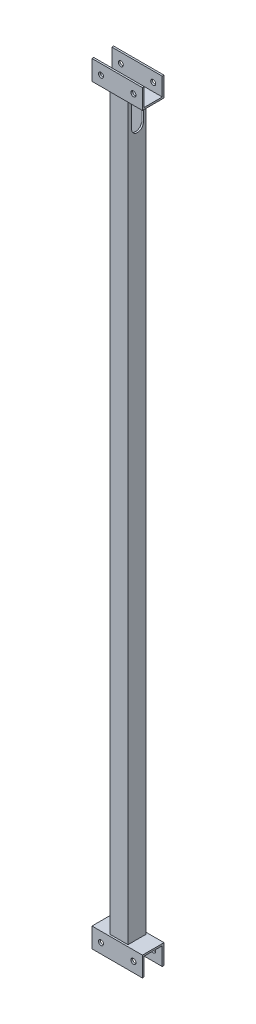
SolidWorks part; units mm, degrees
ref_plane "Front Plane" through (0, 0, 0) normal (0, 0, 1) x (1, 0, 0)
ref_plane "Top Plane" through (0, 0, 0) normal (0, 1, 0) x (1, 0, 0)
ref_plane "Right Plane" through (0, 0, 0) normal (1, 0, 0) x (0, 0, -1)
sketch "Sketch1" plane through (0, 0, 0) normal (0, 1, 0) x (1, 0, 0)
  line L1 (70, -15) -> (70, 45)
  line L2 (-70, -15) -> (-70, 45)
  line L3 (-70, 45) -> (70, 45)
  line L4 (-70, -15) -> (70, -15)
  point P4 (0, 0)
  dimension "D1" = 140
  dimension "D2" = 60
extrude "Boss-Extrude1" add sketch "Sketch1" against normal blind 5
sketch "Sketch2" plane through (0, -5, 0) normal (0, -1, 0) x (1, 0, 0)
  line L0 (-70, 15) -> (70, 15) construction
  line L1 (-70, 15) -> (70, 15)
  line L3 (-70, 10) -> (-70, 15)
  line L4 (70, 10) -> (70, 15)
  line L5 (70, 15) -> (70, -45) construction
  line L10 (-70, 10) -> (70, 10)
  line L15 (70, 15) -> (70, -45)
  line L16 (-930, -15) -> (49070, -15) construction
  line L17 (-70, -40) -> (70, -40)
  line L18 (-70, -40) -> (-70, -45)
  line L19 (-70, -45) -> (70, -45)
  line L20 (70, -40) -> (70, -45)
  point P6 (70, -15)
  line M6 (70, 15) -> (-70, 15)
  line M7 (-70, 15) -> (-70, -45)
  line M9 (70, -45) -> (70, 15)
  dimension "D1" = 140
  dimension "D2" = 5
sketch "Sketch3" plane through (0, 0, 15) normal (0, 0, 1) x (1, 0, 0)
  line L0 (0, -1000) -> (0, 49000) construction
  line L1 (0, 0) -> (0, -55) construction
  line L2 (45, -27.5) -> (-45, -27.5) construction
  point P8 (0, -27.5)
extrude "Boss-Extrude3" add sketch "Sketch2" along normal blind 50 contours L10 M7 M9 M6 | L19 L20 L17 L18
sketch "Sketch4" plane through (0, 0, 15) normal (0, 0, 1) x (1, 0, 0)
  line L4 (70, 0) -> (-70, 0)
  line L5 (-70, 0) -> (-70, -55)
  line L6 (-70, -55) -> (70, -55)
  line L7 (70, -55) -> (70, 0)
  line L8 (70, 0) -> (-70, 0)
  circle A0 centre (-45, -27.5) radius 7
  circle A1 centre (45, -27.5) radius 7
  point P2 (0, 0)
  point P4 (0, -27.5)
  dimension "D2" = 14
  dimension "D1" = 0
extrude "Cut-Extrude1" cut sketch "Sketch4" against normal through all contours A0 | A1
sketch "Sketch5" plane through (0, 0, 0) normal (0, 1, 0) x (1, 0, 0)
  line L0 (70, -15) -> (70, 45) construction
  line L1 (70, -15) -> (70, 45)
  line L2 (-1070, 15) -> (48930, 15) construction
  line L3 (0, -1015) -> (0, 48985) construction
  line L4 (20, -5) -> (20, 35)
  line L5 (25, -10) -> (-25, -10)
  line L6 (-70, -15) -> (70, -15)
  line L7 (70, -15) -> (70, 45)
  line L8 (70, 45) -> (-70, 45)
  line L9 (-70, 45) -> (-70, -15)
  line L10 (-70, -15) -> (70, -15)
  line L11 (70, -15) -> (70, 45)
  line L12 (70, 45) -> (-70, 45)
  line L13 (-70, 45) -> (-70, -15)
  line L14 (25, -10) -> (25, 40)
  line L15 (25, 40) -> (-25, 40)
  line L16 (-25, -10) -> (-25, 40)
  line L17 (25, -10) -> (-25, 40) construction
  line L18 (25, 40) -> (-25, -10) construction
  line L19 (20, 35) -> (-20, 35)
  line L20 (-20, -5) -> (-20, 35)
  line L21 (20, -5) -> (-20, -5)
  point P9 (-70, 15)
  point P10 (0, 15)
  dimension "D2" = 50
  dimension "D3" = 50
  dimension "D1" = 0
extrude "Boss-Extrude4" add sketch "Sketch5" along normal blind 1015 contours L16 L5 L14 L15 L4 L21 L20 L19
mirror "Mirror1" about plane through (0, 1015, 0) normal (0, 1, 0) of bodies 106
sketch "Sketch6" plane through (0, 0, -40) normal (0, 0, -1) x (-1, 0, 0)
  line L0 (-15, 2030) -> (-15, 1983)
  line L5 (-15, 2030) -> (15, 2030)
  line L6 (-70, 2030) -> (70, 2030) construction
  line L7 (15, 2030) -> (15, 1983)
  arc A0 (-15, 1983) -> (15, 1983) centre (0, 1983) ccw
  point P5 (-2.5, 2030)
  point P22 (0, 2030)
sketch "Sketch8" plane through (-25, 0, 0) normal (-1, 0, 0) x (0, 0, 1)
  line L0 (-32.5875, 2030) -> (-32.5875, 1955.0852)
  line L1 (-45, 2030) -> (15, 2030) construction
  line L2 (0, 1955.0852) -> (0, 2030)
  line L3 (0, 2030) -> (-32.5875, 2030)
  arc A0 (-32.5875, 1955.0852) -> (0, 1955.0852) centre (-16.2938, 1955.0852) ccw
extrude "Cut-Extrude3" cut sketch "Sketch8" against normal through all both and the other way through all
